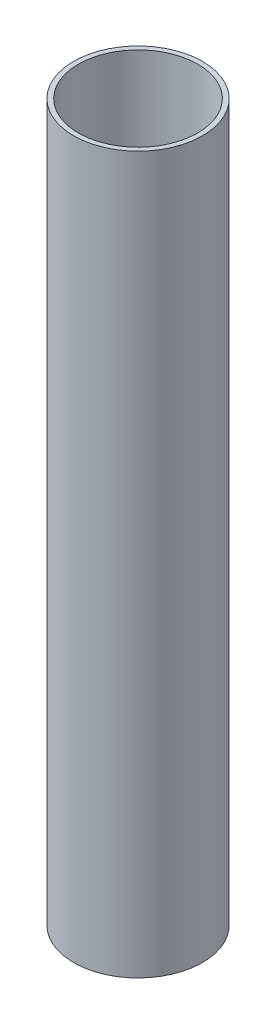
SolidWorks part; units mm, degrees
material "201 Annealed Stainless Steel (SS)"
ref_plane "Front Plane" through (0, 0, 0) normal (0, 0, 1) x (1, 0, 0)
ref_plane "Top Plane" through (0, 0, 0) normal (0, 1, 0) x (1, 0, 0)
ref_plane "Right Plane" through (0, 0, 0) normal (1, 0, 0) x (0, 0, -1)
sketch "Sketch2" plane through (0, 0, 0) normal (0, 1, 0) x (1, 0, 0)
  circle A0 centre (0, 0) radius 6.35
  circle A1 centre (0, 0) radius 6.858
  dimension "D1" = 12.7
  dimension "D2" = 13.716
extrude "Boss-Extrude1" add sketch "Sketch2" along normal blind 76.2
